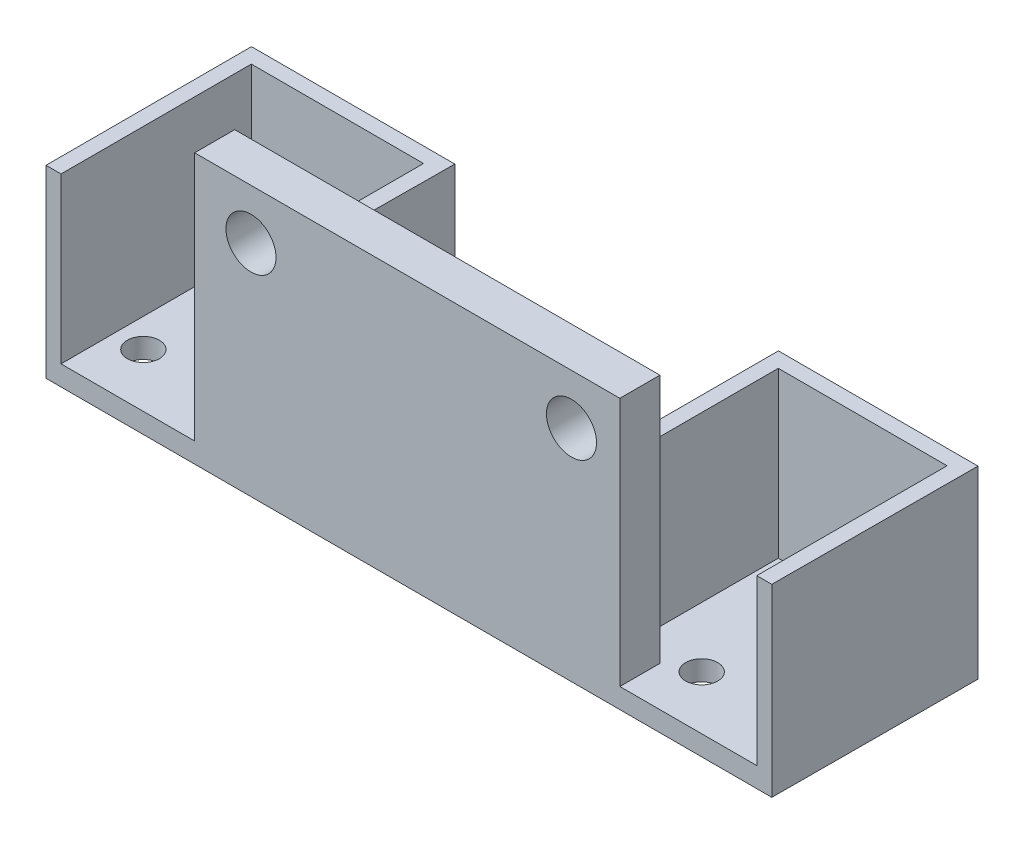
SolidWorks part; units mm, degrees
ref_plane "Ön Düzlem" through (0, 0, 0) normal (0, 0, 1) x (1, 0, 0)
ref_plane "Üst Düzlem" through (0, 0, 0) normal (0, 1, 0) x (1, 0, 0)
ref_plane "Sağ Düzlem" through (0, 0, 0) normal (1, 0, 0) x (0, 0, -1)
sketch "Çizim1" plane through (0, 0, 0) normal (0, 0, 1) x (1, 0, 0)
  line L1 (-11.5, 17.5) -> (11.5, 17.5)
  line L2 (-13.5, 15.5) -> (-13.5, -15.5)
  line L3 (-11.5, -17.5) -> (11.5, -17.5)
  line L4 (13.5, 15.5) -> (13.5, -15.5)
  circle A0 centre (-10, 14) radius 2.5
  circle A1 centre (-10, -14) radius 2.5
  circle A2 centre (10, 14) radius 2.5
  circle A3 centre (10, -14) radius 2.5
  arc A4 (11.5, -17.5) -> (13.5, -15.5) centre (11.5, -15.5) ccw
  arc A5 (-13.5, -15.5) -> (-11.5, -17.5) centre (-11.5, -15.5) ccw
  arc A6 (-11.5, 17.5) -> (-13.5, 15.5) centre (-11.5, 15.5) ccw
  arc A7 (11.5, 17.5) -> (13.5, 15.5) centre (11.5, 15.5) cw
  point P0 (0, 0)
  point P16 (13.5, -17.5)
  point P21 (-13.5, 17.5)
  point P24 (13.5, 17.5)
  dimension "D3" = 5
  dimension "D4" = 5
  dimension "D5" = 5
  dimension "D6" = 5
  dimension "D7" = 3.5
  dimension "D8" = 3.5
  dimension "D9" = 3.5
  dimension "D10" = 3.5
  dimension "D11" = 3.5
  dimension "D12" = 3.5
  dimension "D13" = 3.5
  dimension "D14" = 3.5
  dimension "D15" = 2
  dimension "D1" = 27
  dimension "D2" = 35
extrude "Yükseklik-Ekstrüzyon1" add sketch "Çizim1" along normal blind 2
sketch "Çizim2" plane through (0, 0, 0) normal (0, 0, -1) x (-1, 0, 0)
  line L0 (13.5, 15.5) -> (38.5, 15.5)
  line L1 (38.5, 15.5) -> (38.5, -15.5)
  line L2 (38.5, -15.5) -> (13.5, -15.5)
  line L3 (13.5, -15.5) -> (13.5, 15.5)
  dimension "D1" = 25
extrude "Yükseklik-Ekstrüzyon2" add sketch "Çizim2" against normal blind 2
sketch "Çizim3" plane through (0, 0, 0) normal (0, 0, -1) x (-1, 0, 0)
  line L0 (26, 15.5) -> (26, 12.3298)
  line L1 (38.5, 15.5) -> (13.5, 15.5) construction
  line L2 (26, 12.3298) -> (26.8882, 12.3298)
  line L3 (26.8882, 12.3298) -> (26.8882, 15.5)
  line L4 (26.8882, 15.5) -> (26, 15.5)
extrude "Kes-Ekstrüzyon1" cut sketch "Çizim3" against normal blind 2
mirror "Aynalama4" about plane through (-26, 15.5, 2) normal (1, 0, 0) of "Yükseklik-Ekstrüzyon1"
sketch "Çizim6" plane through (0, 0, 0) normal (0, 0, -1) x (-1, 0, 0)
  line L0 (-13.5, -15.5) -> (-13.5, 15.5) construction
  line L1 (-13.5, 15.5) -> (-16.5, 15.5)
  line L2 (-13.5, 15.5) -> (-13.5, -15.5)
  line L3 (-13.5, -15.5) -> (-16.5, -15.5)
  line L4 (-16.5, 15.5) -> (-16.5, -15.5)
  line L6 (65.5, 15.5) -> (68.5, 15.5)
  line L7 (65.5, 15.5) -> (65.5, -15.5)
  line L8 (65.5, -15.5) -> (68.5, -15.5)
  line L9 (68.5, 15.5) -> (68.5, -15.5)
  arc A0 (-11.5, 17.5) -> (-13.5, 15.5) centre (-11.5, 15.5) ccw construction
  dimension "D1" = 3
  dimension "D2" = 3
extrude "Yükseklik-Ekstrüzyon3" add sketch "Çizim6" against normal blind 10
sketch "Çizim7" plane through (16.5, 0, 0) normal (1, 0, 0) x (0, 0, -1)
  circle A0 centre (-6.6819, 11.5752) radius 1.6
  circle A1 centre (-6.6819, 0) radius 1.6
  circle A2 centre (-6.6819, -12.0698) radius 1.6
  dimension "D1" = 3.2
  dimension "D2" = 3.2
  dimension "D3" = 3.2
extrude "Kes-Ekstrüzyon2" cut sketch "Çizim7" against normal blind 141
sketch "Çizim8" plane through (0, 0, 0) normal (0, 0, -1) x (-1, 0, 0)
  line L0 (26, 15.5) -> (13.5, 15.5) construction
  line L1 (24.5276, 15.5) -> (29.0801, 15.5)
  line L2 (24.5276, 15.5) -> (24.5276, 9.757)
  line L3 (24.5276, 9.757) -> (29.0801, 9.757)
  line L4 (29.0801, 15.5) -> (29.0801, 9.757)
extrude "Yükseklik-Ekstrüzyon4" add sketch "Çizim8" against normal blind 2
sketch "Çizim9" plane through (0, -15.5, 0) normal (0, -1, 0) x (1, 0, 0)
  line L0 (-13.5, 2) -> (-38.5, 2) construction
  line L1 (-68.5, 10) -> (-65.5, 10)
  line L2 (13.5, 10) -> (16.5, 10)
  arc A0 (-65.5, 10) -> (13.5, 10) centre (-26, 1.6211) cw
  arc A1 (-68.5, 10) -> (16.5, 10) centre (-26, 0.4375) cw
  point P7 (-26, 42)
  point P11 (-26, 44)
  dimension "D1" = 40
  dimension "D2" = 42
extrude "Yükseklik-Ekstrüzyon5" add sketch "Çizim9" against normal up to surface (31 mm away) up to face at (14.7, 15.5, 4.4)
sketch "Çizim10" plane through (0, 0, 0) normal (0, 0, -1) x (-1, 0, 0)
  line L0 (-16.5, 15.5) -> (-16.5, 19.8453)
  line L1 (-16.5, 19.8453) -> (68.5, 19.8453)
  line L2 (68.5, 19.8453) -> (68.5, 15.5)
  line L12 (38.5, 15.5) -> (13.5, 15.5)
  line L13 (11.5, 17.5) -> (-11.5, 17.5)
  line L14 (-13.5, 15.5) -> (-16.5, 15.5)
  line L15 (-16.5, 15.5) -> (-16.5, -15.5)
  line L16 (-16.5, -15.5) -> (-13.5, -15.5)
  line L17 (-11.5, -17.5) -> (11.5, -17.5)
  line L18 (13.5, -15.5) -> (38.5, -15.5)
  line L19 (40.5, -17.5) -> (63.5, -17.5)
  line L20 (65.5, -15.5) -> (68.5, -15.5)
  line L21 (68.5, -15.5) -> (68.5, 15.5)
  line L22 (68.5, 15.5) -> (65.5, 15.5)
  line L23 (63.5, 17.5) -> (40.5, 17.5)
  line L24 (38.5, 15.5) -> (13.5, 15.5)
  line L25 (11.5, 17.5) -> (-11.5, 17.5)
  line L26 (-13.5, 15.5) -> (-16.5, 15.5)
  line L27 (-16.5, 15.5) -> (-16.5, -15.5)
  line L28 (-16.5, -15.5) -> (-13.5, -15.5)
  line L29 (-11.5, -17.5) -> (11.5, -17.5)
  line L30 (13.5, -15.5) -> (38.5, -15.5)
  line L31 (40.5, -17.5) -> (63.5, -17.5)
  line L32 (65.5, -15.5) -> (68.5, -15.5)
  line L33 (68.5, -15.5) -> (68.5, 15.5)
  line L34 (68.5, 15.5) -> (65.5, 15.5)
  line L35 (63.5, 17.5) -> (40.5, 17.5)
  arc A8 (13.5, 15.5) -> (11.5, 17.5) centre (11.5, 15.5) ccw
  arc A9 (-11.5, 17.5) -> (-13.5, 15.5) centre (-11.5, 15.5) ccw
  arc A10 (-13.5, -15.5) -> (-11.5, -17.5) centre (-11.5, -15.5) ccw
  arc A11 (11.5, -17.5) -> (13.5, -15.5) centre (11.5, -15.5) ccw
  arc A12 (38.5, -15.5) -> (40.5, -17.5) centre (40.5, -15.5) ccw
  arc A13 (63.5, -17.5) -> (65.5, -15.5) centre (63.5, -15.5) ccw
  arc A14 (65.5, 15.5) -> (63.5, 17.5) centre (63.5, 15.5) ccw
  arc A15 (40.5, 17.5) -> (38.5, 15.5) centre (40.5, 15.5) ccw
  arc A16 (13.5, 15.5) -> (11.5, 17.5) centre (11.5, 15.5) ccw
  arc A17 (-11.5, 17.5) -> (-13.5, 15.5) centre (-11.5, 15.5) ccw
  arc A18 (-13.5, -15.5) -> (-11.5, -17.5) centre (-11.5, -15.5) ccw
  arc A19 (11.5, -17.5) -> (13.5, -15.5) centre (11.5, -15.5) ccw
  arc A20 (38.5, -15.5) -> (40.5, -17.5) centre (40.5, -15.5) ccw
  arc A21 (63.5, -17.5) -> (65.5, -15.5) centre (63.5, -15.5) ccw
  arc A22 (65.5, 15.5) -> (63.5, 17.5) centre (63.5, 15.5) ccw
  arc A23 (40.5, 17.5) -> (38.5, 15.5) centre (40.5, 15.5) ccw
  line M21 (38.5, 15.5) -> (13.5, 15.5)
  arc M22 (13.5, 15.5) -> (11.5, 17.5) centre (11.5, 15.5) ccw
  line M23 (11.5, 17.5) -> (-11.5, 17.5)
  arc M24 (-11.5, 17.5) -> (-13.5, 15.5) centre (-11.5, 15.5) ccw
  line M25 (-13.5, 15.5) -> (-16.5, 15.5)
  line M37 (68.5, 15.5) -> (65.5, 15.5)
  arc M38 (65.5, 15.5) -> (63.5, 17.5) centre (63.5, 15.5) ccw
  line M39 (63.5, 17.5) -> (40.5, 17.5)
  arc M40 (40.5, 17.5) -> (38.5, 15.5) centre (40.5, 15.5) ccw
  dimension "D1" = 0
extrude "Yükseklik-Ekstrüzyon6" add sketch "Çizim10" against normal up to surface (10 mm away) contours L2 L1 L0 M25 M24 M23 M22 M21 M40 M39 M38 M37
fillet "Radyus1" radius 3 3 edges at (16.5, 19.8453, 5) (-68.5, 19.8453, 5) (-26, 19.8453, 44)
fillet "Radyus2" radius 2 5 edges at (16.5, 0.6726, 0) (15.6213, 18.9666, 0) (-68.5, 0.6726, 0) (-67.6213, 18.9666, 0) (-26, 19.8453, 0)
sketch "Çizim11" plane through (0, 0, 0) normal (0, 0, -1) x (-1, 0, 0)
  line L0 (66.5, -15.5) -> (66.5, 16.8453) construction
  line L1 (39, 11) -> (64, 11)
  line L2 (39, 11) -> (39, -9)
  line L3 (39, -9) -> (64, -9)
  line L4 (64, 11) -> (64, -9)
  line L5 (-12, 11) -> (13, 11)
  line L6 (-12, 11) -> (-12, -9)
  line L7 (-12, -9) -> (13, -9)
  line L8 (13, 11) -> (13, -9)
  line L9 (-14.5, 16.8453) -> (-14.5, -15.5) construction
  circle A0 centre (62, -14) radius 2.5 construction
  circle A1 centre (10, -14) radius 2.5 construction
  dimension "D1" = 25
  dimension "D2" = 20
  dimension "D3" = 5
  dimension "D4" = 5
  dimension "D5" = 25
  dimension "D6" = 2.5
  dimension "D7" = 2.5
  dimension "D8" = 20
extrude "Kes-Ekstrüzyon3" cut sketch "Çizim11" against normal blind 10
sketch "Çizim12" plane through (0, 0, 0) normal (0, 0, -1) x (-1, 0, 0)
  line L0 (11.5, -17.5) -> (40.5, -17.5)
  line L9 (-14.5, 16.8453) -> (-14.5, -15.5)
  line L10 (-14.5, -15.5) -> (-13.5, -15.5)
  line L11 (-11.5, -17.5) -> (11.5, -17.5)
  line L12 (13.5, -15.5) -> (38.5, -15.5)
  line L13 (40.5, -17.5) -> (63.5, -17.5)
  line L14 (65.5, -15.5) -> (66.5, -15.5)
  line L15 (66.5, -15.5) -> (66.5, 16.8453)
  line L16 (65.5, 17.8453) -> (-13.5, 17.8453)
  line L17 (-14.5, 16.8453) -> (-14.5, -15.5)
  line L18 (-14.5, -15.5) -> (-13.5, -15.5)
  line L19 (-11.5, -17.5) -> (11.5, -17.5)
  line L20 (13.5, -15.5) -> (38.5, -15.5)
  line L21 (40.5, -17.5) -> (63.5, -17.5)
  line L22 (65.5, -15.5) -> (66.5, -15.5)
  line L23 (66.5, -15.5) -> (66.5, 16.8453)
  line L24 (65.5, 17.8453) -> (-13.5, 17.8453)
  arc A6 (-13.5, 17.8453) -> (-14.5, 16.8453) centre (-13.5, 16.8453) ccw
  arc A7 (-13.5, -15.5) -> (-11.5, -17.5) centre (-11.5, -15.5) ccw
  arc A8 (11.5, -17.5) -> (13.5, -15.5) centre (11.5, -15.5) ccw
  arc A9 (38.5, -15.5) -> (40.5, -17.5) centre (40.5, -15.5) ccw
  arc A10 (63.5, -17.5) -> (65.5, -15.5) centre (63.5, -15.5) ccw
  arc A11 (66.5, 16.8453) -> (65.5, 17.8453) centre (65.5, 16.8453) ccw
  arc A12 (-13.5, 17.8453) -> (-14.5, 16.8453) centre (-13.5, 16.8453) ccw
  arc A13 (-13.5, -15.5) -> (-11.5, -17.5) centre (-11.5, -15.5) ccw
  arc A14 (11.5, -17.5) -> (13.5, -15.5) centre (11.5, -15.5) ccw
  arc A15 (38.5, -15.5) -> (40.5, -17.5) centre (40.5, -15.5) ccw
  arc A16 (63.5, -17.5) -> (65.5, -15.5) centre (63.5, -15.5) ccw
  arc A17 (66.5, 16.8453) -> (65.5, 17.8453) centre (65.5, 16.8453) ccw
  arc M28 (11.5, -17.5) -> (13.5, -15.5) centre (11.5, -15.5) ccw
  line M29 (13.5, -15.5) -> (38.5, -15.5)
  arc M30 (38.5, -15.5) -> (40.5, -17.5) centre (40.5, -15.5) ccw
  dimension "D1" = 0
extrude "Yükseklik-Ekstrüzyon7" add sketch "Çizim12" against normal up to surface (2 mm away) contours L0 M28 M30 M29
sketch "Çizim13" plane through (0, 0, 2) normal (0, 0, 1) x (1, 0, 0)
  line L0 (-64, -9) -> (-39, -9) construction
  line L1 (-47.6234, -9) -> (-5.1705, -9)
  line L2 (-47.6234, -9) -> (-47.6234, -33.9266)
  line L3 (-47.6234, -33.9266) -> (-5.1705, -33.9266)
  line L4 (-5.1705, -9) -> (-5.1705, -33.9266)
  line L6 (-63.5, -17.5) -> (11.5, -17.5)
  line L7 (13.5, -15.5) -> (13.5, 15.5)
  line L8 (11.5, 17.5) -> (-11.5, 17.5)
  line L9 (-13.5, 15.5) -> (-38.5, 15.5)
  line L10 (-40.5, 17.5) -> (-63.5, 17.5)
  line L11 (-65.5, 15.5) -> (-65.5, -15.5)
  line L12 (-63.5, -17.5) -> (11.5, -17.5)
  line L13 (13.5, -15.5) -> (13.5, 15.5)
  line L14 (11.5, 17.5) -> (-11.5, 17.5)
  line L15 (-13.5, 15.5) -> (-38.5, 15.5)
  line L16 (-40.5, 17.5) -> (-63.5, 17.5)
  line L17 (-65.5, 15.5) -> (-65.5, -15.5)
  circle A0 centre (-42, -14) radius 2.5 construction
  circle A1 centre (-42, -14) radius 2.5
  circle A2 centre (-10, -14) radius 2.5 construction
  circle A3 centre (-10, -14) radius 2.5
  arc A6 (-65.5, -15.5) -> (-63.5, -17.5) centre (-63.5, -15.5) ccw
  arc A7 (11.5, -17.5) -> (13.5, -15.5) centre (11.5, -15.5) ccw
  arc A8 (13.5, 15.5) -> (11.5, 17.5) centre (11.5, 15.5) ccw
  arc A9 (-11.5, 17.5) -> (-13.5, 15.5) centre (-11.5, 15.5) ccw
  arc A10 (-38.5, 15.5) -> (-40.5, 17.5) centre (-40.5, 15.5) ccw
  arc A11 (-63.5, 17.5) -> (-65.5, 15.5) centre (-63.5, 15.5) ccw
  arc A12 (-65.5, -15.5) -> (-63.5, -17.5) centre (-63.5, -15.5) ccw
  arc A13 (11.5, -17.5) -> (13.5, -15.5) centre (11.5, -15.5) ccw
  arc A14 (13.5, 15.5) -> (11.5, 17.5) centre (11.5, 15.5) ccw
  arc A15 (-11.5, 17.5) -> (-13.5, 15.5) centre (-11.5, 15.5) ccw
  arc A16 (-38.5, 15.5) -> (-40.5, 17.5) centre (-40.5, 15.5) ccw
  arc A17 (-63.5, 17.5) -> (-65.5, 15.5) centre (-63.5, 15.5) ccw
  point P30 (-47.6234, -33.9266)
  point P31 (0, 0)
  dimension "D1" = 0
extrude "Yükseklik-Ekstrüzyon10" add sketch "Çizim13" along normal blind 4
sketch "Çizim15" plane through (0, 0, 2) normal (0, 0, -1) x (-1, 0, 0)
  line L0 (47.6234, -33.9266) -> (5.1705, -33.9266) construction
  line L1 (8.3549, -33.9266) -> (11.3549, -33.9266)
  line L2 (8.3549, -33.9266) -> (8.3549, -17.5)
  line L3 (8.3549, -17.5) -> (11.3549, -17.5)
  line L4 (11.3549, -33.9266) -> (11.3549, -17.5)
  line L5 (63.5, -17.5) -> (-11.5, -17.5) construction
  line L7 (-11.5, -17.5) -> (-8.5, -17.5)
  line L8 (-11.5, -17.5) -> (-11.5, -33.9266)
  line L9 (-11.5, -33.9266) -> (-8.5, -33.9266)
  line L10 (-8.5, -17.5) -> (-8.5, -33.9266)
  dimension "D1" = 3
  dimension "D2" = 3
extrude "Yükseklik-Ekstrüzyon11" add sketch "Çizim15" along normal blind 15
sketch "Çizim16" plane through (0, 0, 2) normal (0, 0, -1) x (-1, 0, 0)
  line L0 (47.6234, -17.5) -> (11.3549, -17.5) construction
  line L1 (40.7737, -17.5) -> (43.7737, -17.5)
  line L2 (40.7737, -17.5) -> (40.7737, -33.9266)
  line L3 (40.7737, -33.9266) -> (43.7737, -33.9266)
  line L4 (43.7737, -17.5) -> (43.7737, -33.9266)
  line L5 (47.6234, -33.9266) -> (11.3549, -33.9266) construction
  line L6 (63.5, -17.5) -> (11.3549, -17.5) construction
  line L7 (60.9659, -17.5) -> (63.9659, -17.5)
  line L8 (60.9659, -17.5) -> (60.9659, -33.9266)
  line L9 (60.9659, -33.9266) -> (63.9659, -33.9266)
  line L10 (63.9659, -17.5) -> (63.9659, -33.9266)
  dimension "D1" = 3
  dimension "D2" = 3
extrude "Yükseklik-Ekstrüzyon12" add sketch "Çizim16" along normal blind 15
sketch "Çizim17" plane through (11.5, 0, 0) normal (1, 0, 0) x (0, 0, -1)
  line L1 (13, -17.5) -> (16, -17.5)
  line L2 (13, -17.5) -> (13, -33.9222)
  line L3 (13, -33.9222) -> (16, -33.9222)
  line L4 (16, -17.5) -> (16, -33.9222)
  dimension "D1" = 3
extrude "Yükseklik-Ekstrüzyon13" add sketch "Çizim17" against normal up to surface (75.4659 mm away)
sketch "Çizim18" plane through (0, 0, -13) normal (0, 0, 1) x (1, 0, 0)
  line L4 (-11.3549, -33.9222) -> (-11.3549, -17.5)
  line L5 (-11.3549, -17.5) -> (-40.7737, -17.5)
  line L6 (-40.7737, -17.5) -> (-40.7737, -33.9222)
  line L7 (-40.7737, -33.9222) -> (-11.3549, -33.9222)
  line L8 (-11.3549, -33.9222) -> (-11.3549, -17.5)
  line L9 (-11.3549, -17.5) -> (-40.7737, -17.5)
  line L10 (-40.7737, -17.5) -> (-40.7737, -33.9222)
  line L11 (-40.7737, -33.9222) -> (-11.3549, -33.9222)
  dimension "D1" = 0
extrude "Kes-Ekstrüzyon4" cut sketch "Çizim18" against normal blind 15
sketch "Çizim19" plane through (0, -15.5, 0) normal (0, -1, 0) x (1, 0, 0)
  line L1 (-65.5, 2) -> (13.5, 2)
  line L2 (-65.5, 2) -> (-65.5, 0)
  line L3 (-65.5, 0) -> (13.5, 0)
  line L4 (13.5, 2) -> (13.5, 0)
  line L8 (13.5, 0) -> (14.5, 0)
  line L9 (16.5, 2) -> (16.5, 10)
  line L10 (-68.5, 10) -> (-68.5, 2)
  line L11 (-66.5, 0) -> (-65.5, 0)
  line L12 (-65.5, 0) -> (-65.5, 2)
  line L13 (-65.5, 2) -> (-65.5, 10)
  line L14 (13.5, 10) -> (13.5, 2)
  line L15 (13.5, 2) -> (13.5, 0)
  line L16 (13.5, 0) -> (14.5, 0)
  line L17 (16.5, 2) -> (16.5, 10)
  line L18 (-68.5, 10) -> (-68.5, 2)
  line L19 (-66.5, 0) -> (-65.5, 0)
  line L20 (-65.5, 0) -> (-65.5, 2)
  line L21 (-65.5, 2) -> (-65.5, 10)
  line L22 (13.5, 10) -> (13.5, 2)
  line L23 (13.5, 2) -> (13.5, 0)
  arc A4 (14.5, 0) -> (16.5, 2) centre (14.5, 2) ccw
  arc A5 (16.5, 10) -> (-68.5, 10) centre (-26, 0.4375) ccw
  arc A6 (-68.5, 2) -> (-66.5, 0) centre (-66.5, 2) ccw
  arc A7 (13.5, 10) -> (-65.5, 10) centre (-26, 1.6211) ccw
  arc A8 (14.5, 0) -> (16.5, 2) centre (14.5, 2) ccw
  arc A9 (16.5, 10) -> (-68.5, 10) centre (-26, 0.4375) ccw
  arc A10 (-68.5, 2) -> (-66.5, 0) centre (-66.5, 2) ccw
  arc A11 (13.5, 10) -> (-65.5, 10) centre (-26, 1.6211) ccw
  line M13 (13.5, 0) -> (14.5, 0)
  arc M14 (14.5, 0) -> (16.5, 2) centre (14.5, 2) ccw
  line M15 (16.5, 2) -> (16.5, 10)
  arc M16 (16.5, 10) -> (-68.5, 10) centre (-26, 0.4375) ccw
  line M17 (-68.5, 10) -> (-68.5, 2)
  arc M18 (-68.5, 2) -> (-66.5, 0) centre (-66.5, 2) ccw
  line M19 (-66.5, 0) -> (-65.5, 0)
  line M20 (-65.5, 0) -> (-65.5, 2)
  line M21 (-65.5, 2) -> (-65.5, 10)
  arc M22 (-65.5, 10) -> (13.5, 10) centre (-26, 1.6211) cw
  line M23 (13.5, 10) -> (13.5, 2)
  line M24 (13.5, 2) -> (13.5, 0)
  dimension "D1" = 0
extrude "Kes-Ekstrüzyon5" cut sketch "Çizim19" against normal blind 48 contours M24 M13 M14 M15 M16 M17 M18 M19 M20 M21 M22 M23 | L3 L1 M20 M24
sketch "Çizim20" plane through (0, 0, 0) normal (0, 0, -1) x (-1, 0, 0)
  line L12 (65.5, -15.5) -> (64, -15.5)
  line L13 (60, -15.5) -> (44, -15.5)
  line L14 (40, -15.5) -> (12, -15.5)
  line L15 (8, -15.5) -> (-8, -15.5)
  line L16 (-12, -15.5) -> (-13.5, -15.5)
  line L17 (-11.5, -17.5) -> (-8.5, -17.5)
  line L18 (-8.5, -17.5) -> (8.3549, -17.5)
  line L19 (8.3549, -17.5) -> (11.3549, -17.5)
  line L20 (11.3549, -17.5) -> (40.7737, -17.5)
  line L21 (40.7737, -17.5) -> (43.7737, -17.5)
  line L22 (43.7737, -17.5) -> (60.9659, -17.5)
  line L23 (60.9659, -17.5) -> (63.5, -17.5)
  line L24 (65.5, -15.5) -> (64, -15.5)
  line L25 (60, -15.5) -> (44, -15.5)
  line L26 (40, -15.5) -> (12, -15.5)
  line L27 (8, -15.5) -> (-8, -15.5)
  line L28 (-12, -15.5) -> (-13.5, -15.5)
  line L29 (-11.5, -17.5) -> (-8.5, -17.5)
  line L30 (-8.5, -17.5) -> (8.3549, -17.5)
  line L31 (8.3549, -17.5) -> (11.3549, -17.5)
  line L32 (11.3549, -17.5) -> (40.7737, -17.5)
  line L33 (40.7737, -17.5) -> (43.7737, -17.5)
  line L34 (43.7737, -17.5) -> (60.9659, -17.5)
  line L35 (60.9659, -17.5) -> (63.5, -17.5)
  arc A6 (63.5, -17.5) -> (65.5, -15.5) centre (63.5, -15.5) ccw
  arc A7 (60, -15.5) -> (64, -15.5) centre (62, -14) ccw
  arc A8 (40, -15.5) -> (44, -15.5) centre (42, -14) ccw
  arc A9 (8, -15.5) -> (12, -15.5) centre (10, -14) ccw
  arc A10 (-12, -15.5) -> (-8, -15.5) centre (-10, -14) ccw
  arc A11 (-13.5, -15.5) -> (-11.5, -17.5) centre (-11.5, -15.5) ccw
  arc A12 (63.5, -17.5) -> (65.5, -15.5) centre (63.5, -15.5) ccw
  arc A13 (60, -15.5) -> (64, -15.5) centre (62, -14) ccw
  arc A14 (40, -15.5) -> (44, -15.5) centre (42, -14) ccw
  arc A15 (8, -15.5) -> (12, -15.5) centre (10, -14) ccw
  arc A16 (-12, -15.5) -> (-8, -15.5) centre (-10, -14) ccw
  arc A17 (-13.5, -15.5) -> (-11.5, -17.5) centre (-11.5, -15.5) ccw
  dimension "D1" = 0
extrude "Kes-Ekstrüzyon6" cut sketch "Çizim20" against normal up to surface (2 mm away)
sketch "Çizim21" plane through (0, 19.8453, 0) normal (0, 1, 0) x (1, 0, 0)
  line L3 (13.5, -9.6606) -> (13.5, -2)
  line L4 (13.5, -2) -> (-65.5, -2)
  line L5 (-65.5, -2) -> (-65.5, -9.6606)
  line L6 (13.5, -9.6606) -> (13.5, -2)
  line L7 (13.5, -2) -> (-65.5, -2)
  line L8 (-65.5, -2) -> (-65.5, -9.6606)
  arc A1 (-65.5, -9.6606) -> (13.5, -9.6606) centre (-26, -0.4375) ccw
  arc A2 (-65.5, -9.6606) -> (13.5, -9.6606) centre (-26, -0.4375) ccw
  dimension "D1" = 0
sketch "Çizim22" plane through (0, 0, 2) normal (0, 0, -1) x (-1, 0, 0)
  line L6 (65.5, 15.5) -> (65.5, 19.8453)
  line L7 (65.5, 19.8453) -> (-13.5, 19.8453)
  line L8 (-13.5, 19.8453) -> (-13.5, 15.5)
  line L9 (-11.5, 17.5) -> (11.5, 17.5)
  line L10 (13.5, 15.5) -> (38.5, 15.5)
  line L11 (40.5, 17.5) -> (63.5, 17.5)
  line L12 (65.5, 15.5) -> (65.5, 19.8453)
  line L13 (65.5, 19.8453) -> (-13.5, 19.8453)
  line L14 (-13.5, 19.8453) -> (-13.5, 15.5)
  line L15 (-11.5, 17.5) -> (11.5, 17.5)
  line L16 (13.5, 15.5) -> (38.5, 15.5)
  line L17 (40.5, 17.5) -> (63.5, 17.5)
  arc A4 (65.5, 15.5) -> (63.5, 17.5) centre (63.5, 15.5) ccw
  arc A5 (-11.5, 17.5) -> (-13.5, 15.5) centre (-11.5, 15.5) ccw
  arc A6 (13.5, 15.5) -> (11.5, 17.5) centre (11.5, 15.5) ccw
  arc A7 (40.5, 17.5) -> (38.5, 15.5) centre (40.5, 15.5) ccw
  arc A8 (65.5, 15.5) -> (63.5, 17.5) centre (63.5, 15.5) ccw
  arc A9 (-11.5, 17.5) -> (-13.5, 15.5) centre (-11.5, 15.5) ccw
  arc A10 (13.5, 15.5) -> (11.5, 17.5) centre (11.5, 15.5) ccw
  arc A11 (40.5, 17.5) -> (38.5, 15.5) centre (40.5, 15.5) ccw
  dimension "D1" = 0
extrude "Kes-Ekstrüzyon10" cut sketch "Çizim22" against normal blind 58
sketch "Çizim27" plane through (0, -33.9222, 0) normal (0, -1, 0) x (1, 0, 0)
  line L0 (-47.6234, 6) -> (-5.1705, 6) construction
  line L1 (-40.7737, -16) -> (-64.1025, -16)
  line L2 (-40.7737, -16) -> (-40.7737, 6)
  line L3 (-40.7737, 6) -> (-64.1025, 6)
  line L4 (-64.1025, -16) -> (-64.1025, 6)
  line L5 (11.5, -16) -> (-11.3549, -16)
  line L6 (11.5, -16) -> (11.5, 6)
  line L7 (11.5, 6) -> (-11.3549, 6)
  line L8 (-11.3549, -16) -> (-11.3549, 6)
extrude "Yükseklik-Ekstrüzyon16" add sketch "Çizim27" along normal blind 2
sketch "Çizim28" plane through (0, 0, 2) normal (0, 0, 1) x (1, 0, 0)
  line L4 (-63.9659, -17.5) -> (-63.9659, -33.9222)
  line L5 (-63.9659, -33.9222) -> (-60.9659, -33.9222)
  line L6 (-60.9659, -33.9222) -> (-60.9659, -17.5)
  line L7 (-60.9659, -17.5) -> (-63.9659, -17.5)
  line L8 (-63.9659, -17.5) -> (-63.9659, -33.9222)
  line L9 (-63.9659, -33.9222) -> (-60.9659, -33.9222)
  line L10 (-60.9659, -33.9222) -> (-60.9659, -17.5)
  line L11 (-60.9659, -17.5) -> (-63.9659, -17.5)
  line L12 (8.5, -17.5) -> (8.5, -33.9222)
  line L13 (8.5, -33.9222) -> (11.5, -33.9222)
  line L14 (11.5, -33.9222) -> (11.5, -17.5)
  line L15 (11.5, -17.5) -> (8.5, -17.5)
  line L16 (8.5, -17.5) -> (8.5, -33.9222)
  line L17 (8.5, -33.9222) -> (11.5, -33.9222)
  line L18 (11.5, -33.9222) -> (11.5, -17.5)
  line L19 (11.5, -17.5) -> (8.5, -17.5)
  dimension "D1" = 0
  dimension "D2" = 0
extrude "Yükseklik-Ekstrüzyon17" add sketch "Çizim28" along normal up to surface (4 mm away)
sketch "Çizim30" plane through (0, -35.9222, 0) normal (0, -1, 0) x (1, 0, 0)
  line L0 (-11.3549, 6) -> (-11.3549, -16) construction
  line L2 (-40.7737, -16) -> (-40.7737, 6) construction
  line L3 (-64.1025, 6) -> (-64.1025, -16) construction
  line L4 (11.5, -16) -> (11.5, 6) construction
  circle A0 centre (-58.1025, 0.6433) radius 1.6
  circle A1 centre (5.5, 0.6433) radius 1.6
  circle A2 centre (-49.7737, 0.6433) radius 1.6
  circle A3 centre (-2.3549, 0.6433) radius 1.6
  dimension "D1" = 3.2
  dimension "D2" = 3.2
  dimension "D3" = 3.2
  dimension "D4" = 3.2
  dimension "D5" = 9
  dimension "D6" = 9
  dimension "D7" = 6
  dimension "D8" = 6
extrude "Kes-Ekstrüzyon13" cut sketch "Çizim30" against normal blind 10
sketch "Çizim31" plane through (0, -33.9266, 0) normal (0, -1, 0) x (1, 0, 0)
  line L4 (-11.3549, 2) -> (-11.3549, 6)
  line L5 (-11.3549, 6) -> (-40.7737, 6)
  line L6 (-40.7737, 6) -> (-40.7737, 2)
  line L7 (-40.7737, 2) -> (-11.3549, 2)
  line L8 (-11.3549, 2) -> (-11.3549, 6)
  line L9 (-11.3549, 6) -> (-40.7737, 6)
  line L10 (-40.7737, 6) -> (-40.7737, 2)
  line L11 (-40.7737, 2) -> (-11.3549, 2)
  dimension "D1" = 0
extrude "Yükseklik-Ekstrüzyon18" add sketch "Çizim31" along normal up to surface (1.9956 mm away)
sketch "Çizim32" plane through (0, -17.5, 0) normal (0, 1, 0) x (1, 0, 0)
  line L0 (-62.4659, -6) -> (-62.4659, 14.5154)
  line L1 (-62.4659, 14.5154) -> (-42.1602, 14.5154)
  line L2 (-42.1602, 14.5154) -> (-42.2737, -2)
  line L3 (-9.8549, -2) -> (-9.8549, 14.5154)
  line L4 (-9.8549, 14.5154) -> (10.0715, 14.5154)
  line L5 (10.0715, 14.5154) -> (10, -6)
  line L8 (11.5, 16) -> (-11.3549, 16)
  line L9 (-11.3549, 16) -> (-11.3549, -2)
  line L10 (-11.3549, -2) -> (-8.3549, -2)
  line L11 (-8.3549, -2) -> (-8.3549, 13)
  line L12 (-8.3549, 13) -> (8.5, 13)
  line L13 (8.5, 13) -> (8.5, -6)
  line L14 (8.5, -6) -> (11.5, -6)
  line L15 (11.5, -6) -> (11.5, 16)
  line L16 (11.5, 16) -> (-11.3549, 16)
  line L17 (-11.3549, 16) -> (-11.3549, -2)
  line L18 (-11.3549, -2) -> (-8.3549, -2)
  line L19 (-8.3549, -2) -> (-8.3549, 13)
  line L20 (-8.3549, 13) -> (8.5, 13)
  line L21 (8.5, 13) -> (8.5, -6)
  line L22 (8.5, -6) -> (11.5, -6)
  line L23 (11.5, -6) -> (11.5, 16)
  line L24 (-63.9659, 16) -> (-63.9659, -6)
  line L25 (-63.9659, -6) -> (-60.9659, -6)
  line L26 (-60.9659, -6) -> (-60.9659, 13)
  line L27 (-60.9659, 13) -> (-43.7737, 13)
  line L28 (-43.7737, 13) -> (-43.7737, -2)
  line L29 (-43.7737, -2) -> (-40.7737, -2)
  line L30 (-40.7737, -2) -> (-40.7737, 16)
  line L31 (-40.7737, 16) -> (-63.9659, 16)
  line L32 (-63.9659, 16) -> (-63.9659, -6)
  line L33 (-63.9659, -6) -> (-60.9659, -6)
  line L34 (-60.9659, -6) -> (-60.9659, 13)
  line L35 (-60.9659, 13) -> (-43.7737, 13)
  line L36 (-43.7737, 13) -> (-43.7737, -2)
  line L37 (-43.7737, -2) -> (-40.7737, -2)
  line L38 (-40.7737, -2) -> (-40.7737, 16)
  line L39 (-40.7737, 16) -> (-63.9659, 16)
  line M17 (11.5, 16) -> (-11.3549, 16)
  line M18 (-11.3549, 16) -> (-11.3549, -2)
  line M19 (-11.3549, -2) -> (-8.3549, -2)
  line M23 (8.5, -6) -> (11.5, -6)
  line M24 (11.5, -6) -> (11.5, 16)
  dimension "D1" = 0
  dimension "D2" = 0
extrude "Kes-Ekstrüzyon14" cut sketch "Çizim32" against normal blind 28 contours L38 L39 L32 L33 L0 L1 L2 L37 | L4 L5 L3 M23 M24 M17 M18 M19
sketch "Çizim33" plane through (-64.1025, 0, 0) normal (-1, 0, 0) x (0, 0, 1)
  line L4 (6, -33.9222) -> (-16, -33.9222)
  line L5 (-16, -33.9222) -> (-16, -35.9222)
  line L6 (-16, -35.9222) -> (6, -35.9222)
  line L7 (6, -35.9222) -> (6, -33.9222)
  line L8 (6, -33.9222) -> (-16, -33.9222)
  line L9 (-16, -33.9222) -> (-16, -35.9222)
  line L10 (-16, -35.9222) -> (6, -35.9222)
  line L11 (6, -35.9222) -> (6, -33.9222)
  dimension "D1" = 0
extrude "Kes-Ekstrüzyon15" cut sketch "Çizim33" against normal blind 1
